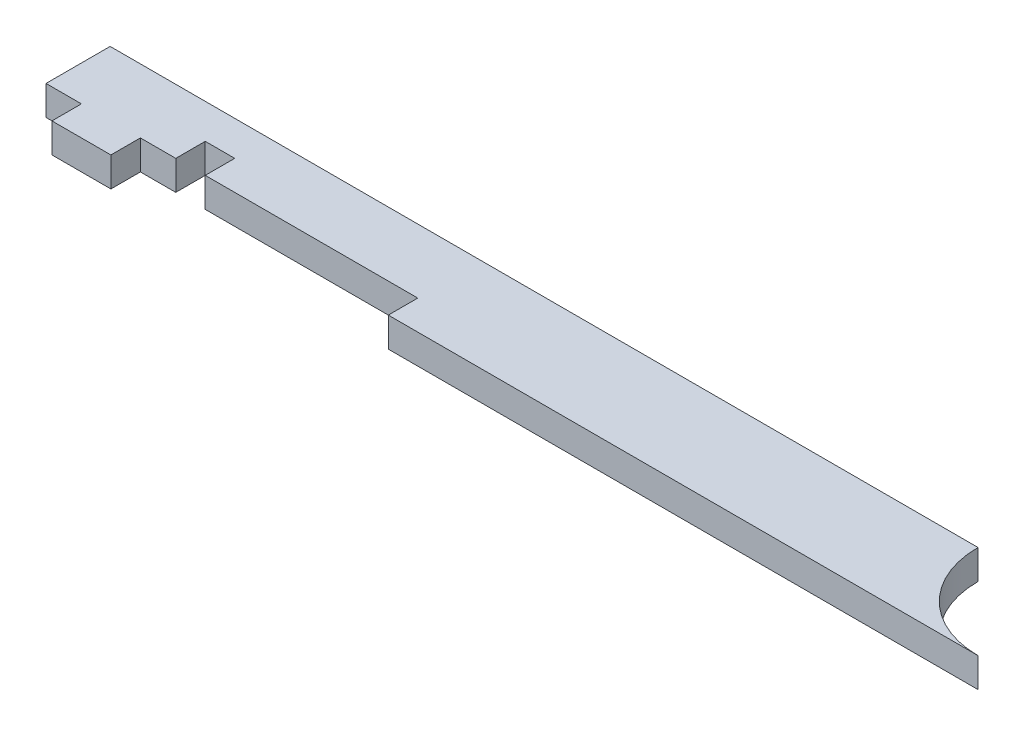
SolidWorks part; units mm, degrees
ref_plane "Front Plane" through (0, 0, 0) normal (1, 0, 0) x (0, 1, 0)
ref_plane "Top Plane" through (0, 0, 0) normal (0, 0, 1) x (0, 1, 0)
ref_plane "Right Plane" through (0, 0, 0) normal (0, 1, 0) x (-1, 0, 0)
sketch "Sketch1" plane through (0, 0, 0) normal (0, 1, 0) x (-1, 0, 0)
  line L0 (-9.76, 0) -> (163.045, 0)
  line L1 (0, 15.875) -> (100, 15.875)
  line L2 (-9.76, 0) -> (152.04, 0)
  line L3 (152.04, 0) -> (152.04, 10.875) construction
  line L4 (100, 15.875) -> (100, 10.875)
  line L9 (152.04, 10.875) -> (152.04, 13.375) construction
  line L10 (147.04, 10.875) -> (141.04, 10.875)
  line L11 (100, 10.875) -> (163.045, 10.875)
  line L12 (163.045, 10.875) -> (163.045, 0)
  line L13 (147.04, 10.875) -> (157.04, 10.875)
  line L14 (147.04, 10.875) -> (147.04, 15.875)
  line L15 (147.04, 15.875) -> (157.04, 15.875)
  line L16 (157.04, 10.875) -> (157.04, 15.875)
  line L17 (147.04, 10.875) -> (157.04, 15.875) construction
  line L18 (147.04, 15.875) -> (157.04, 10.875) construction
  line L19 (141.04, 10.875) -> (141.04, 5.875)
  line L20 (141.04, 5.875) -> (136.04, 5.875)
  line L21 (136.04, 5.875) -> (136.04, 10.875)
  arc A0 (15.875, 0) -> (0, 15.875) centre (0, 0) ccw
  dimension "D1" = 31.75
  dimension "D2" = 172.805
  dimension "D3" = 152.04
  dimension "D4" = 5
  dimension "D5" = 100
  dimension "D6" = 10
  dimension "D7" = 5
  dimension "D8" = 2.5
  dimension "D9" = 5
  dimension "D10" = 5
  dimension "D11" = 6
extrude "Boss-Extrude1" add sketch "Sketch1" along normal mid plane 5 contours A0 L2 L0 L12 L11 L4 L1 | L11 L16 L15 L14
